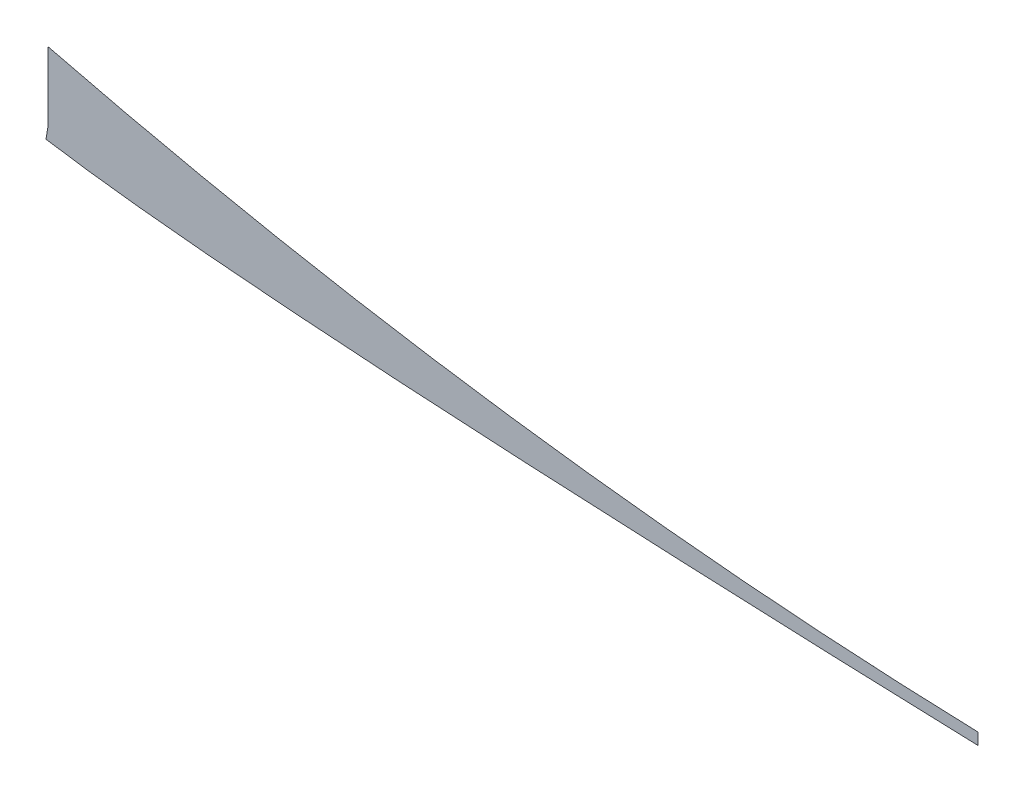
SolidWorks part; units mm, degrees
ref_plane "Front Plane" through (0, 0, 0) normal (0, 0, 1) x (1, 0, 0)
ref_plane "Top Plane" through (0, 0, 0) normal (0, 1, 0) x (1, 0, 0)
ref_plane "Right Plane" through (0, 0, 0) normal (1, 0, 0) x (0, 0, -1)
sketch "Sketch1" plane through (0, 0, 0) normal (0, 0, 1) x (1, 0, 0)
  line L0 (-2508.0244, 162.0162) -> (-2508.0244, 12.0162)
  line L1 (-508.0244, -114.544) -> (-508.0244, -139.5557)
  line L2 (-2508.0244, 12.0162) -> (-2512.0431, -12.6587)
  line L3 (975.7674, -126.4275) -> (975.7674, -101.373)
  line L4 (-2508.0244, 12.0162) -> (-2512.0431, -12.6587)
  line L5 (975.7674, -126.4275) -> (975.7674, -101.373)
  arc A0 (-508.0244, -114.544) -> (-2508.0244, 162.0162) centre (-218.7617, 9347.2939) cw
  spline S2 degree 3 poles (-6454.5938, 654.8266) (-2679.9259, 21.8706) (-2615.1536, 3.7256) (-2498.0428, -14.9032) (-2487.8361, -16.4895) (-2475.3324, -18.375) (-2458.3336, -20.8637) (-2436.4762, -23.9285) (-2409.3029, -27.5342) (-2381.214, -31.0693) (-2342.5806, -35.6905) (-2292.1476, -41.2975) (-2228.4421, -47.7643) (-2161.7936, -53.9783) (-2092.4467, -59.9479) (-1996.7192, -67.5927) (-1871.5631, -76.5793) (-1714.5686, -86.5176) (-1552.7616, -95.674) (-1388.1075, -104.1126) (-1250.1388, -110.5995) (-1140.2607, -115.4933) (-1058.3256, -119.0245) (-977.0535, -122.427) (-897.2422, -125.6742) (-818.7127, -128.7595) (-715.5547, -132.6501) (-589.2496, -137.0801) (-441.1109, -141.6494) (-295.695, -145.4108) (-152.3566, -148.2965) (-10.4989, -150.2182) (130.4752, -151.0881) (271.1761, -150.7798) (412.21, -149.1666) (554.2654, -146.0765) (698.1098, -141.2998) (820.2292, -135.6915) (1749.8876, -83.0796) (2865.1169, 98.3937) (4867.2241, 755.6905) knots 0.150231 0.150231 0.150231 0.150231 0.257796 0.259745 0.263642 0.267539 0.271436 0.279231 0.287025 0.294819 0.302614 0.318203 0.333791 0.34938 0.364969 0.380557 0.411735 0.442912 0.47409 0.505267 0.536445 0.552033 0.567622 0.583211 0.5988 0.614388 0.629977 0.661154 0.692332 0.723509 0.754687 0.785864 0.817042 0.848219 0.879397 0.910574 0.941751 0.972929 0.988518 1.523779 1.523779 1.523779 1.523779 only from (-2512.0431, -12.6587) to (975.7674, -126.4275)
  spline S3 degree 3 poles (4887.5404, 702.9336) (2680.6744, 87.552) (1616.7887, -73.49) (704.536, -116.0261) (560.5486, -120.8946) (418.37, -124.0613) (230.1742, -126.2974) (-4.2222, -125.8049) (-241.5717, -121.7799) (-435.6236, -116.7956) (-583.8946, -112.2437) (-735.6055, -106.9397) (-865.5648, -101.9378) (-958.7687, -98.1518) (-1012.7749, -95.9095) (-1094.326, -92.4747) (-1217.9524, -87.0792) (-1383.8076, -79.2935) (-1548.7608, -70.8533) (-1764.8871, -58.6426) (-1971.3229, -44.8694) (-3178.2725, 54.8392) (-3277.35, 236.5319) (1427.353, 604.618) knots -0.492362 -0.492362 -0.492362 -0.492362 0.028062 0.059312 0.090562 0.121812 0.153062 0.215562 0.278062 0.309312 0.340562 0.371812 0.403062 0.418687 0.4265 0.434312 0.465562 0.496812 0.528062 0.559312 0.621812 0.653062 1.35898 1.35898 1.35898 1.35898 only from (975.7674, -101.373) to (-2508.0244, 12.0162)
  spline S4 degree 3 poles (-2512.0431, -12.6587) (-2510.0545, -12.9826) (-2506.0914, -13.6229) (-2498.0428, -14.9032) (-2487.8361, -16.4895) (-2475.3324, -18.375) (-2458.3336, -20.8637) (-2436.4762, -23.9285) (-2409.3029, -27.5342) (-2381.214, -31.0693) (-2342.5806, -35.6905) (-2292.1476, -41.2975) (-2228.4421, -47.7643) (-2161.7936, -53.9783) (-2092.4467, -59.9479) (-1996.7192, -67.5927) (-1871.5631, -76.5793) (-1714.5686, -86.5176) (-1552.7616, -95.674) (-1388.1075, -104.1126) (-1250.1388, -110.5995) (-1140.2607, -115.4933) (-1058.3256, -119.0245) (-977.0535, -122.427) (-897.2422, -125.6742) (-818.7127, -128.7595) (-715.5547, -132.6501) (-589.2496, -137.0801) (-441.1109, -141.6494) (-295.695, -145.4108) (-152.3566, -148.2965) (-10.4989, -150.2182) (130.4752, -151.0881) (271.1761, -150.7798) (412.21, -149.1666) (554.2654, -146.0765) (698.1098, -141.2998) (820.2292, -135.6915) (913.2681, -130.4261) (957.0766, -127.661) (975.7674, -126.4275) knots 0.255848 0.255848 0.255848 0.255848 0.257796 0.259745 0.263642 0.267539 0.271436 0.279231 0.287025 0.294819 0.302614 0.318203 0.333791 0.34938 0.364969 0.380557 0.411735 0.442912 0.47409 0.505267 0.536445 0.552033 0.567622 0.583211 0.5988 0.614388 0.629977 0.661154 0.692332 0.723509 0.754687 0.785864 0.817042 0.848219 0.879397 0.910574 0.941751 0.972929 0.988518 1 1 1 1
  spline S5 degree 3 poles (975.7674, -101.373) (933.9571, -104.1395) (842.6289, -109.5872) (704.536, -116.0261) (560.5486, -120.8946) (418.37, -124.0613) (230.1742, -126.2974) (-4.2222, -125.8049) (-241.5717, -121.7799) (-435.6236, -116.7956) (-583.8946, -112.2437) (-735.6055, -106.9397) (-865.5648, -101.9378) (-958.7687, -98.1518) (-1012.7749, -95.9095) (-1094.326, -92.4747) (-1217.9524, -87.0792) (-1383.8076, -79.2935) (-1548.7608, -70.8533) (-1764.8871, -58.6426) (-1971.3229, -44.8694) (-2254.3194, -21.4905) (-2413.8411, -3.3232) (-2508.0244, 12.0162) knots 0.002322 0.002322 0.002322 0.002322 0.028062 0.059312 0.090562 0.121812 0.153062 0.215562 0.278062 0.309312 0.340562 0.371812 0.403062 0.418687 0.4265 0.434312 0.465562 0.496812 0.528062 0.559312 0.621812 0.653062 0.746812 0.746812 0.746812 0.746812
  dimension "D2" = 150
  dimension "D3" = 2000
  dimension "D1" = 0
extrude "Boss-Extrude1" add sketch "Sketch1" along normal blind 0.0002 contours S5 A0 L0 | L1 S5 L4 S4
